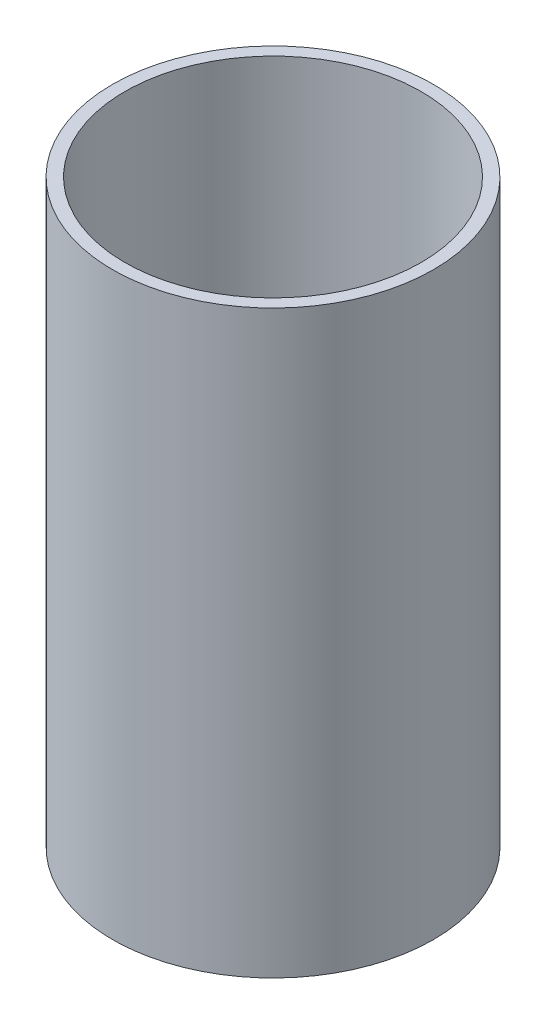
SolidWorks part; units mm, degrees
material "Acrylic (Medium-high impact)"
ref_plane "Front Plane" through (0, 0, 0) normal (0, 0, 1) x (1, 0, 0)
ref_plane "Top Plane" through (0, 0, 0) normal (0, 1, 0) x (1, 0, 0)
ref_plane "Right Plane" through (0, 0, 0) normal (1, 0, 0) x (0, 0, -1)
other "Center of Mass"
sketch "Sketch1" plane through (0, 0, 0) normal (0, 0, 1) x (1, 0, 0)
  line L0 (0, 0) -> (0, 423.3576) construction
  line L1 (76.2, 0) -> (82.55, 0)
  line L2 (76.2, 0) -> (76.2, 298.45)
  line L3 (76.2, 298.45) -> (82.55, 298.45)
  line L4 (82.55, 0) -> (82.55, 298.45)
  dimension "D1" = 76.2
  dimension "D2" = 298.45
  dimension "D3" = 6.35
revolve "Revolve1" add sketch "Sketch1" angle 360 about L0
